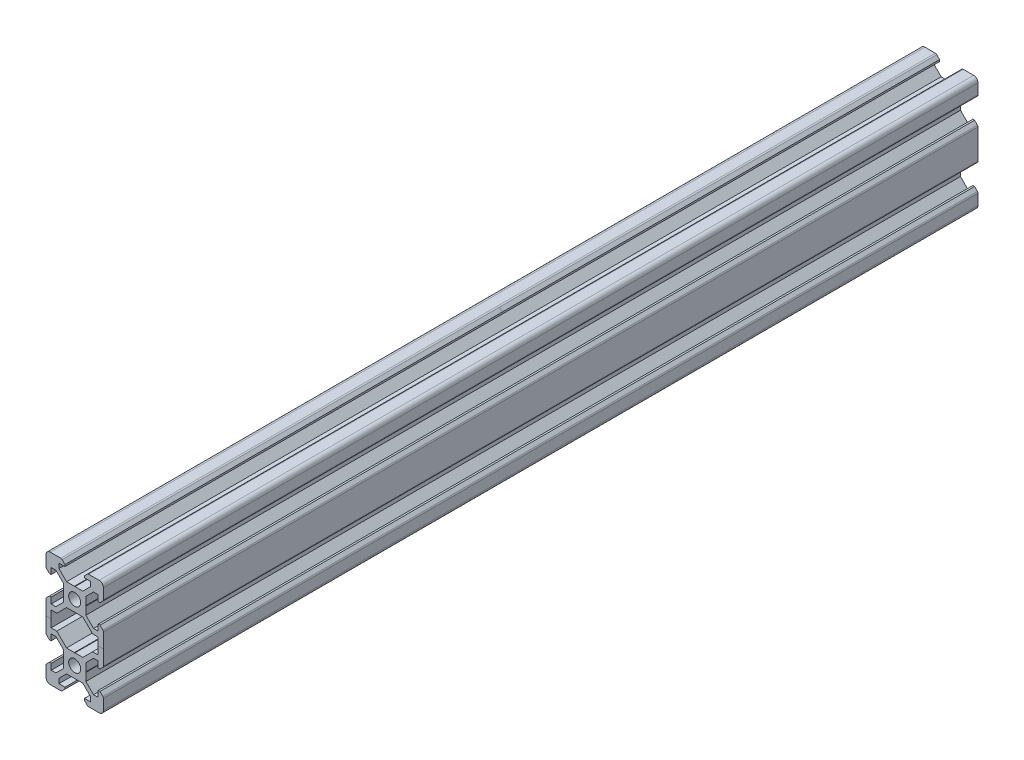
SolidWorks part; units mm, degrees
material "6063-T5"
ref_plane "Front" through (0, 0, 0) normal (0, 0, 1) x (1, 0, 0)
ref_plane "Top" through (0, 0, 0) normal (0, 1, 0) x (1, 0, 0)
ref_plane "Right" through (0, 0, 0) normal (1, 0, 0) x (0, 0, -1)
sketch "Sketch1" plane through (0, 0, 0) normal (0, 0, 1) x (1, 0, 0)
  line L0 (-8.5, 10) -> (-10, 8.5) construction
  line L1 (-8.5, 10) -> (-4.8628, 10)
  line L2 (-10, 8.5) -> (-10, 4.8628)
  line L4 (10, 8.5) -> (10, 4.8628)
  line L5 (-10, 10) -> (10, -10) construction
  line L6 (-10, -10) -> (10, 10) construction
  line L7 (8.2, -5.5) -> (8.2, -3.3865)
  line L8 (-8.2, -5.5) -> (-8.2, -3.3865)
  line L9 (-5.5, 8.2) -> (-3.3865, 8.2)
  line L10 (-8.2, -12.7) -> (-8.2, -7.3)
  line L11 (-3.9005, 2.8395) -> (-6.561, 5.5)
  line L12 (-6.561, 5.5) -> (-8.2, 5.5)
  line L13 (-2.8395, -3.9005) -> (-0.1, -3.9005)
  line L14 (-3.9005, -2.8395) -> (-3.9005, -0.1)
  line L15 (-2.8395, 3.9005) -> (-0.1, 3.9005)
  line L16 (3.9005, -2.8395) -> (3.9005, -0.1)
  line L17 (-8.2, 3.3865) -> (-8.81, 3.3865)
  line L18 (-8.81, 3.3865) -> (-9.7976, 4.3741)
  line L19 (8.5, 10) -> (10, 8.5) construction
  line L20 (-2.8395, 3.9005) -> (-5.5, 6.561)
  line L21 (-5.5, 6.561) -> (-5.5, 8.2)
  line L22 (-3.3865, 8.2) -> (-3.3865, 8.81)
  line L23 (-3.3865, 8.81) -> (-4.3741, 9.7976)
  line L24 (0, 24.069) -> (0, -33.8154) construction
  line L25 (3.3865, 8.81) -> (4.3741, 9.7976)
  line L26 (3.3865, 8.2) -> (3.3865, 8.81)
  line L27 (5.5, 6.561) -> (5.5, 8.2)
  line L28 (2.8395, 3.9005) -> (5.5, 6.561)
  line L29 (3.3865, 8.2) -> (5.5, 8.2)
  line L30 (4.8628, 10) -> (8.5, 10)
  line L31 (-0.1, 3.9005) -> (0, 3.8005)
  line L32 (0.1, 3.9005) -> (0, 3.8005)
  line L33 (0.1, 3.9005) -> (2.8395, 3.9005)
  line L34 (25.9287, 0) -> (-28.3459, 0) construction
  line L35 (-0.1, -3.9005) -> (0, -3.8005)
  line L36 (0.1, -3.9005) -> (0, -3.8005)
  line L37 (0.1, -3.9005) -> (2.8395, -3.9005)
  line L38 (-3.9005, 0.1) -> (-3.8005, 0)
  line L39 (-3.8005, 0) -> (-3.9005, -0.1)
  line L40 (-3.9005, 0.1) -> (-3.9005, 2.8395)
  line L41 (3.9005, 0.1) -> (3.8005, 0)
  line L42 (3.8005, 0) -> (3.9005, -0.1)
  line L43 (3.9005, 0.1) -> (3.9005, 2.8395)
  line L44 (8.81, 3.3865) -> (9.7976, 4.3741)
  line L45 (8.2, 3.3865) -> (8.81, 3.3865)
  line L46 (6.561, 5.5) -> (8.2, 5.5)
  line L47 (3.9005, 2.8395) -> (6.561, 5.5)
  line L48 (2.8395, -3.9005) -> (5.5, -6.561)
  line L49 (3.9005, -2.8395) -> (6.561, -5.5)
  line L50 (-2.8395, -3.9005) -> (-5.5, -6.561)
  line L51 (-3.9005, -2.8395) -> (-6.561, -5.5)
  line L52 (6.561, -5.5) -> (8.2, -5.5)
  line L53 (-6.561, -5.5) -> (-8.2, -5.5)
  line L54 (-8.81, -3.3865) -> (-9.7976, -4.3741)
  line L55 (-8.2, -3.3865) -> (-8.81, -3.3865)
  line L56 (8.81, -3.3865) -> (9.7976, -4.3741)
  line L57 (8.2, -3.3865) -> (8.81, -3.3865)
  line L58 (8.2, 3.3865) -> (8.2, 5.5)
  line L59 (10, -4.8628) -> (10, -15.1372)
  line L60 (-8.2, 3.3865) -> (-8.2, 5.5)
  line L61 (-10, -4.8628) -> (-10, -15.1372)
  line L62 (-28.3459, -10) -> (-10, -10) construction
  line L63 (-3.9005, -20.1) -> (-3.9005, -22.8395)
  line L64 (-3.9005, -20.1) -> (-3.8005, -20)
  line L65 (-3.8005, -20) -> (-3.9005, -19.9)
  line L66 (3.9005, -20.1) -> (3.9005, -22.8395)
  line L67 (3.9005, -20.1) -> (3.8005, -20)
  line L68 (3.8005, -20) -> (3.9005, -19.9)
  line L69 (6.561, -14.5) -> (8.2, -14.5)
  line L70 (3.9005, -17.1605) -> (6.561, -14.5)
  line L71 (3.9005, -17.1605) -> (3.9005, -19.9)
  line L72 (-3.9005, -17.1605) -> (-3.9005, -19.9)
  line L73 (-3.9005, -17.1605) -> (-6.561, -14.5)
  line L74 (-6.561, -14.5) -> (-8.2, -14.5)
  line L75 (-8.2, -16.6135) -> (-8.81, -16.6135)
  line L76 (-8.81, -16.6135) -> (-9.7976, -15.6259)
  line L77 (8.2, -16.6135) -> (8.81, -16.6135)
  line L78 (8.81, -16.6135) -> (9.7976, -15.6259)
  line L79 (-2.8395, -16.0995) -> (-5.5, -13.439)
  line L80 (-2.8395, -16.0995) -> (-0.1, -16.0995)
  line L81 (-0.1, -16.0995) -> (0, -16.1995)
  line L82 (0.1, -16.0995) -> (0, -16.1995)
  line L83 (0.1, -16.0995) -> (2.8395, -16.0995)
  line L84 (2.8395, -16.0995) -> (5.5, -13.439)
  line L85 (-8.2, -16.6135) -> (-8.2, -14.5)
  line L86 (8.2, -16.6135) -> (8.2, -14.5)
  line L87 (2.8395, -23.9005) -> (5.5, -26.561)
  line L88 (-2.8395, -23.9005) -> (-5.5, -26.561)
  line L89 (-0.1, -23.9005) -> (0, -23.8005)
  line L90 (0.1, -23.9005) -> (0, -23.8005)
  line L91 (0.1, -23.9005) -> (2.8395, -23.9005)
  line L92 (-2.8395, -23.9005) -> (-0.1, -23.9005)
  line L93 (-10, -28.5) -> (-10, -24.8628)
  line L94 (10, -28.5) -> (10, -24.8628)
  line L95 (8.81, -23.3865) -> (9.7976, -24.3741)
  line L96 (-8.81, -23.3865) -> (-9.7976, -24.3741)
  line L97 (-8.2, -23.3865) -> (-8.81, -23.3865)
  line L98 (8.2, -23.3865) -> (8.81, -23.3865)
  line L99 (8.2, -23.3865) -> (8.2, -25.5)
  line L100 (-8.2, -23.3865) -> (-8.2, -25.5)
  line L101 (-6.561, -25.5) -> (-8.2, -25.5)
  line L102 (6.561, -25.5) -> (8.2, -25.5)
  line L103 (3.9005, -22.8395) -> (6.561, -25.5)
  line L104 (-3.9005, -22.8395) -> (-6.561, -25.5)
  line L105 (-5.5, -28.2) -> (-3.3865, -28.2)
  line L106 (3.3865, -28.2) -> (5.5, -28.2)
  line L107 (3.3865, -28.2) -> (3.3865, -28.81)
  line L108 (3.3865, -28.81) -> (4.3741, -29.7976)
  line L109 (-3.3865, -28.2) -> (-3.3865, -28.81)
  line L110 (-3.3865, -28.81) -> (-4.3741, -29.7976)
  line L111 (-8.5, -30) -> (-4.8628, -30)
  line L112 (4.8628, -30) -> (8.5, -30)
  line L113 (-5.5, -26.561) -> (-5.5, -28.2)
  line L114 (5.5, -26.561) -> (5.5, -28.2)
  line L115 (-6.239, -7.3) -> (-8.2, -7.3)
  line L116 (-5.5, -6.561) -> (-6.239, -7.3)
  line L117 (6.239, -7.3) -> (8.2, -7.3)
  line L118 (5.5, -6.561) -> (6.239, -7.3)
  line L119 (-6.239, -12.7) -> (-8.2, -12.7)
  line L120 (-5.5, -13.439) -> (-6.239, -12.7)
  line L121 (5.5, -13.439) -> (6.239, -12.7)
  line L122 (6.239, -12.7) -> (8.2, -12.7)
  line L123 (8.2, -12.7) -> (8.2, -7.3)
  line L125 (10, -10) -> (25.9287, -10) construction
  circle A0 centre (0, 0) radius 2.1
  arc A1 (-8.5, 10) -> (-10, 8.5) centre (-8.5, 8.5) ccw
  arc A2 (10, 8.5) -> (8.5, 10) centre (8.5, 8.5) ccw
  arc A3 (-4.3741, 9.7976) -> (-4.8628, 10) centre (-4.8628, 9.3088) ccw
  arc A4 (4.8628, 10) -> (4.3741, 9.7976) centre (4.8628, 9.3088) ccw
  circle A5 centre (0, -20) radius 2.1
  arc A6 (9.7976, 4.3741) -> (10, 4.8628) centre (9.3088, 4.8628) ccw
  arc A7 (-10, 4.8628) -> (-9.7976, 4.3741) centre (-9.3088, 4.8628) ccw
  arc A8 (-10, -4.8628) -> (-9.7976, -4.3741) centre (-9.3088, -4.8628) cw
  arc A9 (9.7976, -4.3741) -> (10, -4.8628) centre (9.3088, -4.8628) cw
  arc A10 (-10, -15.1372) -> (-9.7976, -15.6259) centre (-9.3088, -15.1372) ccw
  arc A11 (9.7976, -15.6259) -> (10, -15.1372) centre (9.3088, -15.1372) ccw
  arc A12 (-10, -24.8628) -> (-9.7976, -24.3741) centre (-9.3088, -24.8628) cw
  arc A13 (9.7976, -24.3741) -> (10, -24.8628) centre (9.3088, -24.8628) cw
  arc A14 (4.8628, -30) -> (4.3741, -29.7976) centre (4.8628, -29.3088) cw
  arc A15 (-4.3741, -29.7976) -> (-4.8628, -30) centre (-4.8628, -29.3088) cw
  arc A16 (-8.5, -30) -> (-10, -28.5) centre (-8.5, -28.5) cw
  arc A17 (10, -28.5) -> (8.5, -30) centre (8.5, -28.5) cw
  point P17 (-9.25, 9.25)
  point P21 (9.25, 9.25)
  dimension "D2" = 4.2
  dimension "D4" = 1.5
  dimension "D3" = 20
  dimension "D5" = 0.529
  dimension "D6" = 6.773
  dimension "D7" = 90
  dimension "D8" = 11
  dimension "D9" = 0.61
  dimension "D10" = 0.1
  dimension "D11" = 0.1
  dimension "D12" = 0.1
  dimension "D13" = 0.1
  dimension "D14" = 5.679
  dimension "D15" = 1.639
  dimension "D16" = 1.8
  dimension "D17" = 90
  dimension "D18" = 6.773
  dimension "D19" = 90
  dimension "D20" = 20
  dimension "D21" = 1.8
extrude "Boss-Extrude2" add sketch "Sketch1" along normal blind 304.8
sketch "Sketch2" plane through (0, 0, 0) normal (0, 0, -1) x (-1, 0, 0)
  line L0 (-10, -10) -> (10, -10)
  line L1 (-10, -15.1372) -> (-10, -4.8628) construction
  line L2 (10, -4.8628) -> (10, -15.1372) construction
split line "SideFixture1 - SplitLine"
sketch "Sketch3" plane through (0, 0, 304.8) normal (0, 0, 1) x (1, 0, 0)
  line L0 (-10, -10) -> (10, -10)
  line L1 (-10, -4.8628) -> (-10, -15.1372) construction
  line L2 (10, -15.1372) -> (10, -4.8628) construction
split line "SideFixture2 - SplitLine"
sketch "Sketch4" plane through (0, 10, 0) normal (0, 1, 0) x (1, 0, 0)
  line L0 (-8.5, -152.4) -> (8.5, -152.4)
  line L1 (-8.5, -304.8) -> (-8.5, 0) construction
  line L2 (8.5, -304.8) -> (8.5, 0) construction
split line "SideFixture3 - SplitLine"
